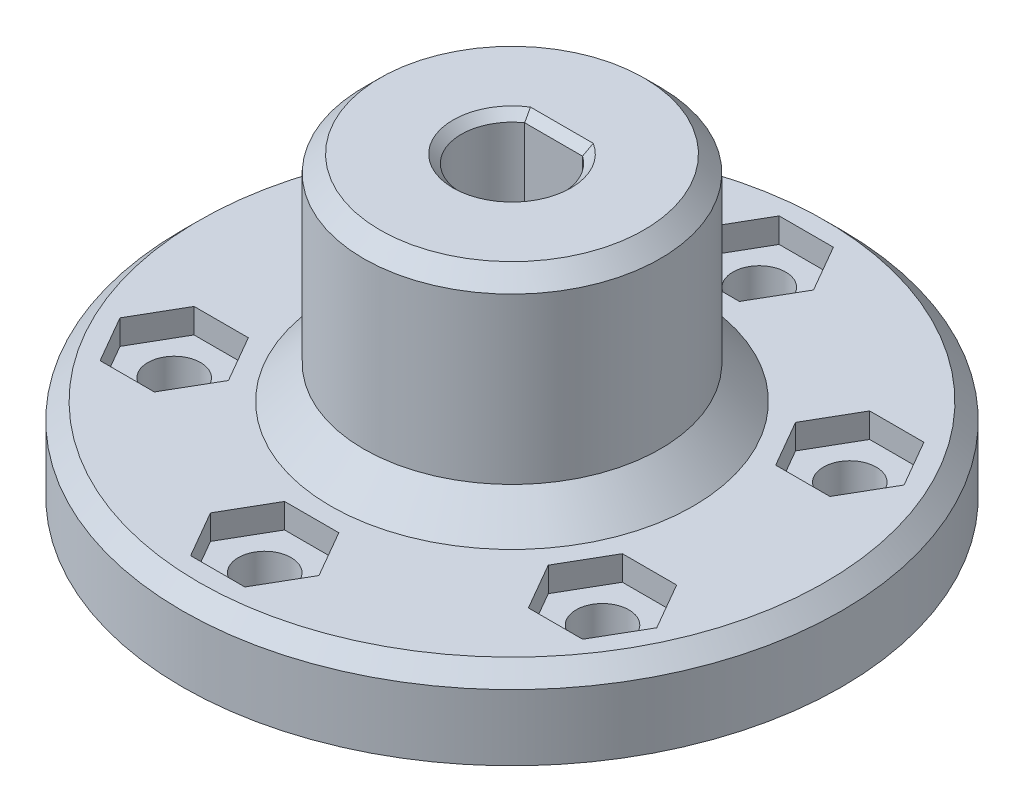
SolidWorks part; units mm, degrees
material "PLA"
ref_plane "Front" through (0, 0, 0) normal (0, 0, 1) x (1, 0, 0)
ref_plane "Top" through (0, 0, 0) normal (0, 1, 0) x (1, 0, 0)
ref_plane "Right" through (0, 0, 0) normal (1, 0, 0) x (0, 0, -1)
sketch "Sketch1" plane through (0, 0, 0) normal (0, 1, 0) x (1, 0, 0)
  circle A0 centre (0, 0) radius 20
  dimension "D1" = 40
extrude "Boss-Extrude1" add sketch "Sketch1" along normal blind 5
sketch "Sketch2" plane through (0, 5, 0) normal (0, 1, 0) x (1, 0, 0)
  circle A0 centre (0, 15) radius 1.6
  circle A1 centre (12.9904, 7.5) radius 1.6
  circle A2 centre (12.9904, -7.5) radius 1.6
  circle A3 centre (0, -15) radius 1.6
  circle A4 centre (-12.9904, -7.5) radius 1.6
  circle A5 centre (-12.9904, 7.5) radius 1.6
  point P19 (0, 0)
  dimension "D1" = 3.2
  dimension "D2" = 15
  dimension "D3" = 6
extrude "Cut-Extrude1" cut sketch "Sketch2" against normal through all
sketch "Sketch3" plane through (0, 5, 0) normal (0, 1, 0) x (1, 0, 0)
  circle A0 centre (0, 0) radius 9
  dimension "D1" = 18
extrude "Boss-Extrude2" add sketch "Sketch3" along normal blind 13
sketch "Sketch4" plane through (0, 18, 0) normal (0, 1, 0) x (1, 0, 0)
  line L0 (-1.755, 2.525) -> (1.755, 2.525)
  line L1 (0, 0) -> (0, -3.075) construction
  circle A0 centre (0, 0) radius 3.075
  dimension "D1" = 6.15
  dimension "D2" = 5.6
extrude "Cut-Extrude2" cut sketch "Sketch4" against normal through all
sketch "Sketch5" plane through (0, 18, 0) normal (0, 1, 0) x (1, 0, 0)
  line L1 (-0.5, -9) -> (0.5, -9)
  line L2 (-0.5, -9) -> (-0.5, 4)
  line L3 (-0.5, 4) -> (0.5, 4)
  line L4 (0.5, -9) -> (0.5, 4)
  line L5 (-0.5, -9) -> (0.5, 4) construction
  line L6 (-0.5, 4) -> (0.5, -9) construction
  circle A0 centre (0, 0) radius 9 construction
  point P0 (0, -2.5)
  dimension "D1" = 1
  dimension "D2" = 4
extrude "Cut-Extrude3" [suppressed] cut sketch "Sketch5" against normal blind 12
ref_plane "Plane1" [suppressed] through (9, 0, 0) normal (1, 0, 0) x (0, 0, -1)
sketch "Sketch7" [suppressed] plane through (9, 0, 0) normal (1, 0, 0) x (0, 0, -1)
  line L0 (9, 5) -> (9, 20) construction
  line L1 (9, 8) -> (-8.9861, 8)
  line L2 (9, 8) -> (9, 9)
  line L3 (9, 9) -> (-8.9861, 9)
  line L4 (-8.9861, 8) -> (-8.9861, 9)
  line L5 (-8.9861, 20) -> (-8.9861, 8) construction
  line L6 (-8.9861, 8) -> (-9, 8) construction
  dimension "D1" = 1
extrude "Cut-Extrude4" [suppressed] cut sketch "Sketch7" against normal up to surface (9.5 mm away)
sketch "Sketch8" [suppressed] plane through (9, 0, 0) normal (1, 0, 0) x (0, 0, -1)
  line L0 (-8.9861, 20) -> (-8.9861, 9) construction
  line L1 (-5.9861, 17.5) -> (-8.9861, 17.5)
  line L2 (-8.9861, 17.5) -> (-8.9861, 11.5)
  line L3 (-8.9861, 11.5) -> (-5.9861, 11.5)
  line L4 (9, 9) -> (9, 20) construction
  line L5 (9, 14.5) -> (-17.854, 14.5) construction
  circle A0 centre (-5.9861, 14.5) radius 3
  dimension "D1" = 6
extrude "Cut-Extrude5" [suppressed] cut sketch "Sketch8" against normal blind 6 contours A0 | A0 L1 L2 | A0 L2 L3
mirror "Mirror1" [suppressed] about plane through (0, 0, 0) normal (1, 0, 0)
sketch "Sketch9" [suppressed] plane through (3, 0, 0) normal (1, 0, 0) x (0, 0, -1)
  circle A0 centre (-5.9861, 14.5) radius 2
  arc A1 (-5.9861, 11.5) -> (-5.9861, 17.5) centre (-5.9861, 14.5) ccw construction
  dimension "D1" = 4
extrude "Cut-Extrude6" [suppressed] cut sketch "Sketch9" against normal through all
chamfer "Chamfer3" distance 2 distance2 2 1 edges at (0, 5, 9)
chamfer "Chamfer4" distance 1 angle 45 1 edges at (0, 5, 20)
chamfer "Chamfer5" distance 1 angle 45 1 edges at (0, 18, 9)
chamfer "Chamfer6" distance 0.5 angle 45 2 edges at (0, 18, -2.525) (0, 18, 3.075)
sketch "Sketch10" plane through (0, 5, 0) normal (0, 1, 0) x (1, 0, 0)
  line L0 (0, 0) -> (-12.9904, 7.5) construction
  line L1 (1.6454, 17.85) -> (-1.6454, 17.85)
  line L2 (-1.6454, 17.85) -> (-3.2909, 15)
  line L3 (-3.2909, 15) -> (-1.6454, 12.15)
  line L4 (-1.6454, 12.15) -> (1.6454, 12.15)
  line L5 (1.6454, 12.15) -> (3.2909, 15)
  line L6 (3.2909, 15) -> (1.6454, 17.85)
  line L7 (14.6358, 10.35) -> (11.3449, 10.35)
  line L8 (11.3449, 10.35) -> (9.6995, 7.5)
  line L9 (9.6995, 7.5) -> (11.3449, 4.65)
  line L10 (11.3449, 4.65) -> (14.6358, 4.65)
  line L11 (14.6358, 4.65) -> (16.2813, 7.5)
  line L12 (16.2813, 7.5) -> (14.6358, 10.35)
  line L13 (-11.3449, 10.35) -> (-14.6358, 10.35)
  line L14 (-14.6358, 10.35) -> (-16.2813, 7.5)
  line L15 (-16.2813, 7.5) -> (-14.6358, 4.65)
  line L16 (-14.6358, 4.65) -> (-11.3449, 4.65)
  line L17 (-11.3449, 4.65) -> (-9.6995, 7.5)
  line L18 (-9.6995, 7.5) -> (-11.3449, 10.35)
  line L19 (0, 0) -> (0, 15) construction
  line L20 (0, 0) -> (12.9904, 7.5) construction
  circle A0 centre (0, 15) radius 2.85 construction
  circle A1 centre (12.9904, 7.5) radius 2.85 construction
  circle A2 centre (-12.9904, 7.5) radius 2.85 construction
  dimension "D1" = 5.7
  dimension "D2" = 5.7
  dimension "D3" = 5.7
extrude "Cut-Extrude7" cut sketch "Sketch10" against normal blind 1.5
mirror "Mirror2" about plane through (0, 0, 0) normal (0, 0, 1) of "Cut-Extrude7"
